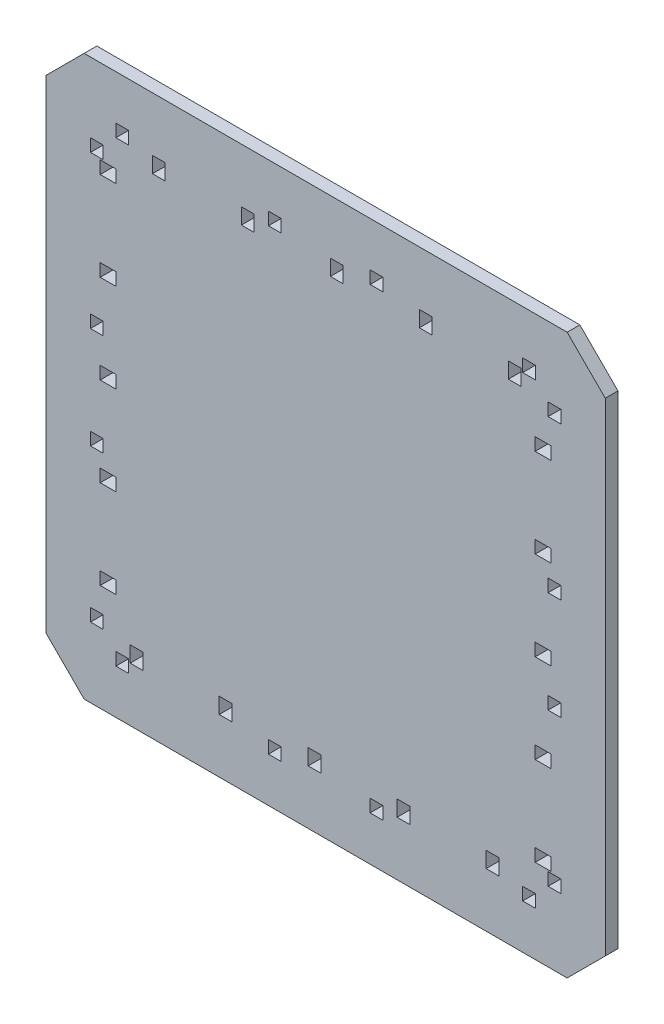
SolidWorks part; units mm, degrees
ref_plane "Front Plane" through (0, 0, 0) normal (0, 0, 1) x (1, 0, 0)
ref_plane "Top Plane" through (0, 0, 0) normal (0, 1, 0) x (1, 0, 0)
ref_plane "Right Plane" through (0, 0, 0) normal (1, 0, 0) x (0, 0, -1)
sketch "Sketch1" plane through (0, 0, 0) normal (0, 0, 1) x (1, 0, 0)
  line L656 (58.5, 283.5) -> (58.5, 286.5)
  line L657 (58.5, 286.5) -> (55.5, 286.5)
  line L658 (55.5, 286.5) -> (55.5, 283.5)
  line L659 (55.5, 283.5) -> (58.5, 283.5)
  line L660 (82.5, 283.5) -> (79.5, 283.5)
  line L661 (79.5, 283.5) -> (79.5, 286.5)
  line L662 (79.5, 286.5) -> (82.5, 286.5)
  line L663 (82.5, 286.5) -> (82.5, 283.5)
  line L664 (22.5, 283.5) -> (19.5, 283.5)
  line L665 (19.5, 283.5) -> (19.5, 286.5)
  line L666 (19.5, 286.5) -> (22.5, 286.5)
  line L667 (22.5, 286.5) -> (22.5, 283.5)
  line L668 (118.5, 283.5) -> (115.5, 283.5)
  line L669 (115.5, 283.5) -> (115.5, 286.5)
  line L670 (115.5, 286.5) -> (118.5, 286.5)
  line L671 (118.5, 286.5) -> (118.5, 283.5)
  line L672 (79.5, 178.5) -> (79.5, 175.5)
  line L673 (79.5, 175.5) -> (82.5, 175.5)
  line L674 (82.5, 175.5) -> (82.5, 178.5)
  line L675 (82.5, 178.5) -> (79.5, 178.5)
  line L676 (55.5, 178.5) -> (58.5, 178.5)
  line L677 (58.5, 178.5) -> (58.5, 175.5)
  line L678 (58.5, 175.5) -> (55.5, 175.5)
  line L679 (55.5, 175.5) -> (55.5, 178.5)
  line L680 (115.5, 178.5) -> (118.5, 178.5)
  line L681 (118.5, 178.5) -> (118.5, 175.5)
  line L682 (118.5, 175.5) -> (115.5, 175.5)
  line L683 (115.5, 175.5) -> (115.5, 178.5)
  line L684 (19.5, 178.5) -> (22.5, 178.5)
  line L685 (22.5, 178.5) -> (22.5, 175.5)
  line L686 (22.5, 175.5) -> (19.5, 175.5)
  line L687 (19.5, 175.5) -> (19.5, 178.5)
  line L688 (16.5, 280.5) -> (16.5, 277.5)
  line L689 (16.5, 277.5) -> (13.5, 277.5)
  line L690 (13.5, 277.5) -> (13.5, 280.5)
  line L691 (13.5, 280.5) -> (16.5, 280.5)
  line L692 (16.5, 184.5) -> (16.5, 181.5)
  line L693 (16.5, 181.5) -> (13.5, 181.5)
  line L694 (13.5, 181.5) -> (13.5, 184.5)
  line L695 (13.5, 184.5) -> (16.5, 184.5)
  line L696 (16.5, 244.5) -> (16.5, 241.5)
  line L697 (16.5, 241.5) -> (13.5, 241.5)
  line L698 (13.5, 241.5) -> (13.5, 244.5)
  line L699 (13.5, 244.5) -> (16.5, 244.5)
  line L700 (16.5, 220.5) -> (13.5, 220.5)
  line L701 (13.5, 220.5) -> (13.5, 217.5)
  line L702 (13.5, 217.5) -> (16.5, 217.5)
  line L703 (16.5, 217.5) -> (16.5, 220.5)
  line L704 (121.5, 181.5) -> (121.5, 184.5)
  line L705 (121.5, 184.5) -> (124.5, 184.5)
  line L706 (124.5, 184.5) -> (124.5, 181.5)
  line L707 (124.5, 181.5) -> (121.5, 181.5)
  line L708 (121.5, 277.5) -> (121.5, 280.5)
  line L709 (121.5, 280.5) -> (124.5, 280.5)
  line L710 (124.5, 280.5) -> (124.5, 277.5)
  line L711 (124.5, 277.5) -> (121.5, 277.5)
  line L712 (121.5, 217.5) -> (121.5, 220.5)
  line L713 (121.5, 220.5) -> (124.5, 220.5)
  line L714 (124.5, 220.5) -> (124.5, 217.5)
  line L715 (124.5, 217.5) -> (121.5, 217.5)
  line L716 (121.5, 241.5) -> (124.5, 241.5)
  line L717 (124.5, 241.5) -> (124.5, 244.5)
  line L718 (124.5, 244.5) -> (121.5, 244.5)
  line L719 (121.5, 244.5) -> (121.5, 241.5)
  line L720 (15.7944, 211.125) -> (19.5388, 211.125)
  line L721 (19.5388, 211.125) -> (19.5388, 214.125)
  line L722 (19.5388, 214.125) -> (15.7944, 214.125)
  line L723 (15.7944, 214.125) -> (15.7944, 211.125)
  line L724 (15.7944, 253.125) -> (19.5388, 253.125)
  line L725 (19.5388, 253.125) -> (19.5388, 256.125)
  line L726 (19.5388, 256.125) -> (15.7944, 256.125)
  line L727 (15.7944, 256.125) -> (15.7944, 253.125)
  line L728 (15.7944, 232.125) -> (19.5388, 232.125)
  line L729 (19.5388, 232.125) -> (19.5388, 235.125)
  line L730 (19.5388, 235.125) -> (15.7944, 235.125)
  line L731 (15.7944, 235.125) -> (15.7944, 232.125)
  line L732 (15.7944, 274.125) -> (19.5388, 274.125)
  line L733 (19.5388, 274.125) -> (19.5388, 277.125)
  line L734 (19.5388, 277.125) -> (15.7944, 277.125)
  line L735 (15.7944, 277.125) -> (15.7944, 274.125)
  line L736 (15.7944, 190.125) -> (19.5388, 190.125)
  line L737 (19.5388, 190.125) -> (19.5388, 193.125)
  line L738 (19.5388, 193.125) -> (15.7944, 193.125)
  line L739 (15.7944, 193.125) -> (15.7944, 190.125)
  line L740 (88.875, 177.7944) -> (88.875, 181.5388)
  line L741 (88.875, 181.5388) -> (85.875, 181.5388)
  line L742 (85.875, 181.5388) -> (85.875, 177.7944)
  line L743 (85.875, 177.7944) -> (88.875, 177.7944)
  line L744 (46.875, 177.7944) -> (46.875, 181.5388)
  line L745 (46.875, 181.5388) -> (43.875, 181.5388)
  line L746 (43.875, 181.5388) -> (43.875, 177.7944)
  line L747 (43.875, 177.7944) -> (46.875, 177.7944)
  line L748 (67.875, 177.7944) -> (67.875, 181.5388)
  line L749 (67.875, 181.5388) -> (64.875, 181.5388)
  line L750 (64.875, 181.5388) -> (64.875, 177.7944)
  line L751 (64.875, 177.7944) -> (67.875, 177.7944)
  line L752 (25.875, 177.7944) -> (25.875, 181.5388)
  line L753 (25.875, 181.5388) -> (22.875, 181.5388)
  line L754 (22.875, 181.5388) -> (22.875, 177.7944)
  line L755 (22.875, 177.7944) -> (25.875, 177.7944)
  line L756 (109.875, 177.7944) -> (109.875, 181.5388)
  line L757 (109.875, 181.5388) -> (106.875, 181.5388)
  line L758 (106.875, 181.5388) -> (106.875, 177.7944)
  line L759 (106.875, 177.7944) -> (109.875, 177.7944)
  line L760 (122.2056, 250.875) -> (118.4612, 250.875)
  line L761 (118.4612, 250.875) -> (118.4612, 247.875)
  line L762 (118.4612, 247.875) -> (122.2056, 247.875)
  line L763 (122.2056, 247.875) -> (122.2056, 250.875)
  line L764 (122.2056, 208.875) -> (118.4612, 208.875)
  line L765 (118.4612, 208.875) -> (118.4612, 205.875)
  line L766 (118.4612, 205.875) -> (122.2056, 205.875)
  line L767 (122.2056, 205.875) -> (122.2056, 208.875)
  line L768 (122.2056, 229.875) -> (118.4612, 229.875)
  line L769 (118.4612, 229.875) -> (118.4612, 226.875)
  line L770 (118.4612, 226.875) -> (122.2056, 226.875)
  line L771 (122.2056, 226.875) -> (122.2056, 229.875)
  line L772 (122.2056, 187.875) -> (118.4612, 187.875)
  line L773 (118.4612, 187.875) -> (118.4612, 184.875)
  line L774 (118.4612, 184.875) -> (122.2056, 184.875)
  line L775 (122.2056, 184.875) -> (122.2056, 187.875)
  line L776 (122.2056, 271.875) -> (118.4612, 271.875)
  line L777 (118.4612, 271.875) -> (118.4612, 268.875)
  line L778 (118.4612, 268.875) -> (122.2056, 268.875)
  line L779 (122.2056, 268.875) -> (122.2056, 271.875)
  line L780 (49.125, 284.2056) -> (49.125, 280.4612)
  line L781 (49.125, 280.4612) -> (52.125, 280.4612)
  line L782 (52.125, 280.4612) -> (52.125, 284.2056)
  line L783 (52.125, 284.2056) -> (49.125, 284.2056)
  line L784 (91.125, 284.2056) -> (91.125, 280.4612)
  line L785 (91.125, 280.4612) -> (94.125, 280.4612)
  line L786 (94.125, 280.4612) -> (94.125, 284.2056)
  line L787 (94.125, 284.2056) -> (91.125, 284.2056)
  line L788 (70.125, 284.2056) -> (70.125, 280.4612)
  line L789 (70.125, 280.4612) -> (73.125, 280.4612)
  line L790 (73.125, 280.4612) -> (73.125, 284.2056)
  line L791 (73.125, 284.2056) -> (70.125, 284.2056)
  line L792 (112.125, 284.2056) -> (112.125, 280.4612)
  line L793 (112.125, 280.4612) -> (115.125, 280.4612)
  line L794 (115.125, 280.4612) -> (115.125, 284.2056)
  line L795 (115.125, 284.2056) -> (112.125, 284.2056)
  line L796 (28.125, 284.2056) -> (28.125, 280.4612)
  line L797 (28.125, 280.4612) -> (31.125, 280.4612)
  line L798 (31.125, 280.4612) -> (31.125, 284.2056)
  line L799 (31.125, 284.2056) -> (28.125, 284.2056)
  line L800 (12, 297) -> (3, 288)
  line L801 (3, 288) -> (3, 174)
  line L802 (3, 174) -> (12, 165)
  line L803 (12, 165) -> (126, 165)
  line L804 (126, 165) -> (135, 174)
  line L805 (135, 174) -> (135, 288)
  line L806 (135, 288) -> (126, 297)
  line L807 (126, 297) -> (12, 297)
extrude "Boss-Extrude1" add sketch "Sketch1" along normal blind 3
